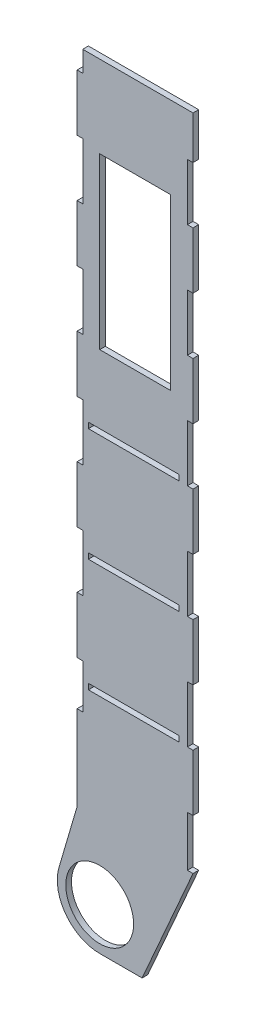
SolidWorks part; units mm, degrees
ref_plane "前视基准面" through (0, 0, 0) normal (0, 0, 1) x (1, 0, 0)
ref_plane "上视基准面" through (0, 0, 0) normal (0, 1, 0) x (1, 0, 0)
ref_plane "右视基准面" through (0, 0, 0) normal (1, 0, 0) x (0, 0, -1)
sketch "草图1" plane through (0, 0, 0) normal (0, 0, 1) x (1, 0, 0)
  line L93 (-8, -48.3425) -> (-6, -48.3425)
  line L100 (-6, -48.3425) -> (-6, -68.3425)
  line L101 (-6, -68.3425) -> (-8, -68.3425)
  line L102 (-8, -68.3425) -> (-8, -88.3425)
  line L103 (-8, -88.3425) -> (-6, -88.3425)
  line L104 (-6, -88.3425) -> (-6, -108.3425)
  line L105 (-6, -108.3425) -> (-8, -108.3425)
  line L106 (-8, -108.3425) -> (-8, -128.3425)
  line L108 (33, -36.2215) -> (31, -36.2215)
  line L109 (31, -36.2215) -> (31, -56.2215)
  line L110 (31, -56.2215) -> (33, -56.2215)
  line L111 (33, -56.2215) -> (33, -76.2215)
  line L112 (33, -76.2215) -> (31, -76.2215)
  line L113 (31, -76.2215) -> (31, -96.2215)
  line L114 (31, -96.2215) -> (33, -96.2215)
  line L117 (33, -96.2215) -> (33, -116.2215)
  line L118 (33, -116.2215) -> (31, -116.2215)
  line L119 (31, -116.2215) -> (31, -136.2215)
  line L120 (31, -136.2215) -> (33, -136.2215)
  line L128 (-4, -56.2215) -> (-4, -54.2215)
  line L129 (-4, -54.2215) -> (28, -54.2215)
  line L130 (28, -54.2215) -> (28, -56.2215)
  line L131 (-4, -56.2215) -> (28, -56.2215)
  line L134 (-4, -94.2215) -> (28, -94.2215)
  line L135 (-4, -96.2215) -> (28, -96.2215)
  line L136 (28, -94.2215) -> (28, -96.2215)
  line L137 (-4, -96.2215) -> (-4, -94.2215)
  line L138 (-4, -134.2215) -> (28, -134.2215)
  line L139 (-4, -136.2215) -> (28, -136.2215)
  line L140 (28, -134.2215) -> (28, -136.2215)
  line L141 (-4, -136.2215) -> (-4, -134.2215)
  line L146 (-8, -174) -> (-14.3926, -195.7746)
  line L148 (0, -215) -> (15, -215)
  line L151 (15, -215) -> (33, -174)
  line L157 (33, 59) -> (33, 49)
  line L158 (33, -36.2215) -> (33, -16.2215)
  line L159 (33, -16.2215) -> (31, -16.2215)
  line L160 (31, -16.2215) -> (31, 3.7785)
  line L161 (31, 3.7785) -> (33, 3.7785)
  line L162 (33, 3.7785) -> (33, 23.7785)
  line L163 (33, 23.7785) -> (31, 23.7785)
  line L164 (31, 23.7785) -> (31, 43.7785)
  line L167 (-8, -48.3425) -> (-8, -28.3425)
  line L168 (-8, -28.3425) -> (-6, -28.3425)
  line L169 (-6, -28.3425) -> (-6, -8.3425)
  line L170 (-6, -8.3425) -> (-8, -8.3425)
  line L171 (-8, -8.3425) -> (-8, 11.6575)
  line L172 (-8, 11.6575) -> (-6, 11.6575)
  line L173 (-6, 11.6575) -> (-6, 31.6575)
  line L174 (-6, 31.6575) -> (-8, 31.6575)
  line L175 (-8, 31.6575) -> (-8, 51.6575)
  line L176 (-8, 51.6575) -> (-6, 51.6575)
  line L177 (-6, 51.6575) -> (-6, 59)
  line L178 (-6, 59) -> (33, 59)
  line L179 (-8, -128.3425) -> (-6, -128.3425)
  line L180 (-6, -128.3425) -> (-6, -144)
  line L181 (-6, -144) -> (-8, -144)
  line L183 (33, -136.2215) -> (33, -156.2215)
  line L184 (33, -156.2215) -> (31, -156.2215)
  line L185 (31, -156.2215) -> (31, -174)
  line L186 (31, -174) -> (33, -174)
  line L187 (-8, -144) -> (-8, -174)
  line L188 (31, 43.7785) -> (33, 43.7785)
  line L189 (33, 43.7785) -> (33, 49)
  line L191 (0, 30) -> (25, 30)
  line L192 (25, 30) -> (25, -30)
  line L194 (0, -30) -> (25, -30)
  line L195 (0, 30) -> (0, -30)
  arc A61 (-14.3926, -195.7746) -> (0, -215) centre (0, -200) ccw
  circle A62 centre (0, -200) radius 12
  dimension "D1" = 3
extrude "凸台-拉伸1" add sketch "草图1" along normal blind 2 contours L146 A61 L148 L151 L186 L185 L184 L183 L120 L119 L118 L117 L114 L113 L112 L111 L110 L109 L108 L158 L159 L160 L161 L162 L163 L164 L188 L189 L157 L178 L177 L176 L175 L174 L173 L172 L171 L170 L169 L168 L167 L93 L100 L101 L102 L103 L104 L105 L106 L179 L180 | A62 | L138 L140 L139 L141 | L134 L136 L135 L137 | L128 L129 L130 L131
